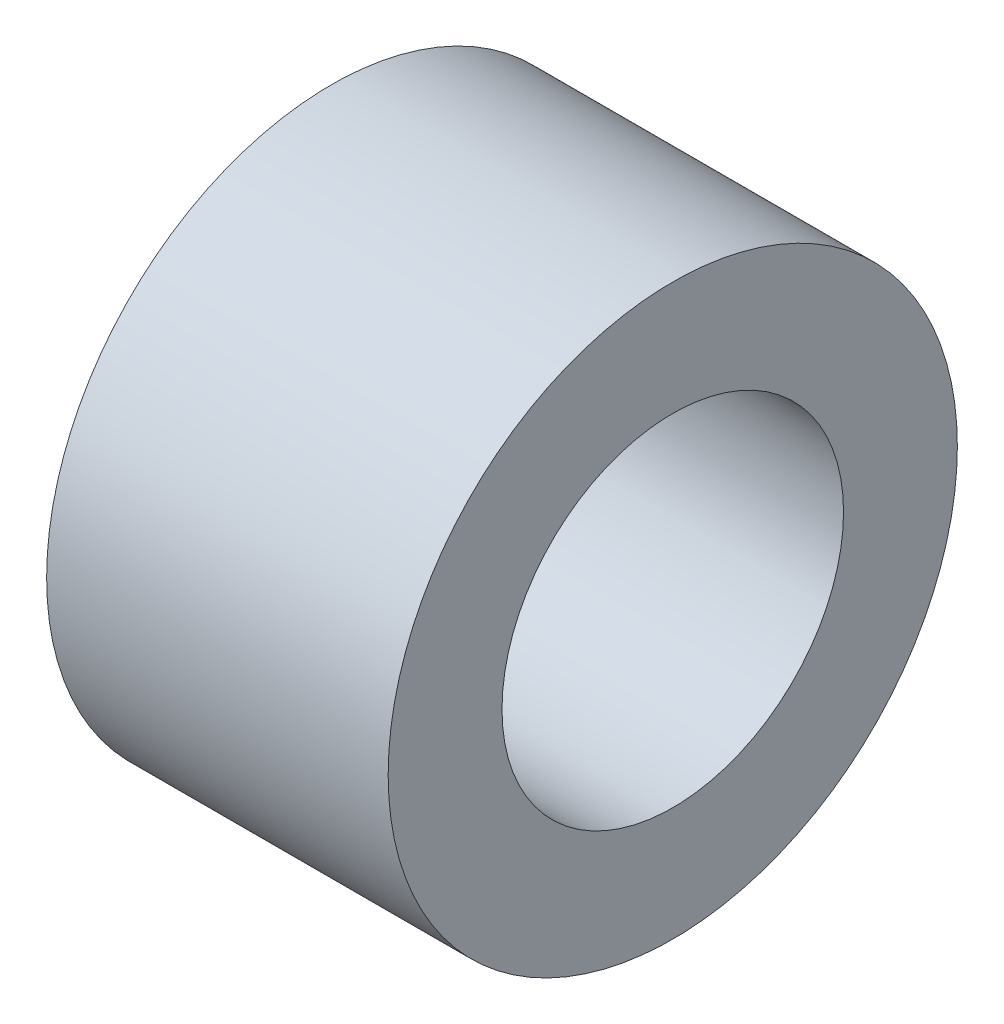
SolidWorks part; units mm, degrees
ref_plane "Front Plane" through (0, 0, 0) normal (0, 0, 1) x (1, 0, 0)
ref_plane "Top Plane" through (0, 0, 0) normal (0, 1, 0) x (1, 0, 0)
ref_plane "Right Plane" through (0, 0, 0) normal (1, 0, 0) x (0, 0, -1)
sketch "Sketch1" plane through (0, 0, 0) normal (0, 0, 1) x (1, 0, 0)
  line L0 (0, 0) -> (15, 0) construction
  line L2 (0, 12.5) -> (15, 12.5)
  line L3 (0, 12.5) -> (0, 7.5)
  line L4 (0, 7.5) -> (15, 7.5)
  line L5 (15, 12.5) -> (15, 7.5)
  dimension "W" = 15
  dimension "D2." = 15
  dimension "D" = 25
revolve "Revolve1" add sketch "Sketch1" angle 360 about L0
